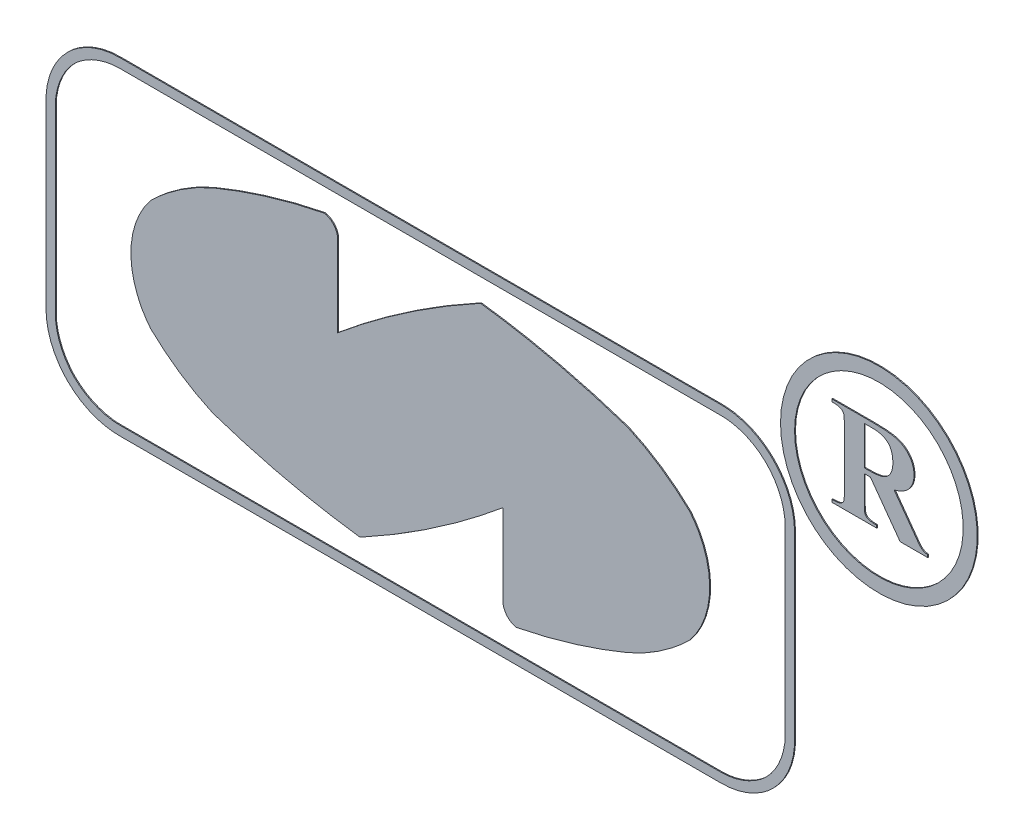
SolidWorks part; units mm, degrees
ref_plane "Спереди" through (0, 0, 0) normal (0, 0, 1) x (1, 0, 0)
ref_plane "Сверху" through (0, 0, 0) normal (0, 1, 0) x (1, 0, 0)
ref_plane "Справа" through (0, 0, 0) normal (1, 0, 0) x (0, 0, -1)
sketch "Эскиз1" plane through (0, 0, 0) normal (0, 0, 1) x (1, 0, 0)
  line L0 (3.1861, 1.7736) -> (-3.2358, 1.7736)
  line L1 (-4.0201, 0.9894) -> (-4.0201, -0.94)
  line L2 (-3.2358, -1.7242) -> (3.1861, -1.7242)
  line L3 (3.97, -0.94) -> (3.97, 0.9894)
  line L4 (-3.233, -1.7326) -> (3.1904, -1.7326)
  line L5 (-4.0213, 0.9865) -> (-4.0213, -0.9443)
  line L6 (3.1904, 1.7748) -> (-3.233, 1.7748)
  line L7 (3.9787, -0.9443) -> (3.9787, 0.9865)
  line L8 (3.1861, 1.6736) -> (-3.2358, 1.6736)
  line L9 (-3.9201, 0.9894) -> (-3.9201, -0.94)
  line L10 (-3.2358, -1.6242) -> (3.1861, -1.6242)
  line L11 (3.87, -0.94) -> (3.87, 0.9894)
  line L12 (4.2935, 1.4733) -> (5.4465, 1.4733) construction
  line L13 (-4.0201, 0.0247) -> (-3.9201, 0.0247) construction
  line L14 (-3.9201, 0.0247) -> (3.87, 0.0247) construction
  line L15 (3.87, 0.0247) -> (3.97, 0.0247) construction
  line L16 (4.87, 1.4733) -> (4.87, 1.9247) construction
  circle A0 centre (4.87, 1.9247) radius 0.9
  circle A1 centre (4.87, 1.9247) radius 1.05
  spline S0 degree 3 poles (-3.2358, 1.7736) (-3.444, 1.7736) (-3.6433, 1.6909) (-3.7904, 1.544) knots 0 0 0 0 0.5 0.5 0.5 0.5
  spline S1 degree 3 poles (-3.7904, 1.544) (-3.9374, 1.3968) (-4.0201, 1.1976) (-4.0201, 0.9894) knots 0.5 0.5 0.5 0.5 1 1 1 1
  spline S2 degree 3 poles (-4.0201, -0.94) (-4.0201, -1.1481) (-3.9374, -1.3474) (-3.7904, -1.4946) knots 0 0 0 0 0.5 0.5 0.5 0.5
  spline S3 degree 3 poles (-3.7904, -1.4946) (-3.6433, -1.6415) (-3.444, -1.7242) (-3.2358, -1.7242) knots 0.5 0.5 0.5 0.5 1 1 1 1
  spline S4 degree 3 poles (3.1861, -1.7242) (3.3941, -1.7242) (3.5937, -1.6415) (3.7405, -1.4946) knots 0 0 0 0 0.5 0.5 0.5 0.5
  spline S5 degree 3 poles (3.7405, -1.4946) (3.8876, -1.3474) (3.97, -1.1481) (3.97, -0.94) knots 0.5 0.5 0.5 0.5 1 1 1 1
  spline S6 degree 3 poles (3.97, 0.9894) (3.97, 1.4226) (3.6193, 1.7736) (3.1861, 1.7736) knots 0 0 0 0 1 1 1 1
  spline S7 degree 3 poles (3.1904, -1.7326) (3.3992, -1.7326) (3.6, -1.6494) (3.7476, -1.5017) knots 0 0 0 0 0.5 0.5 0.5 0.5
  spline S8 degree 3 poles (3.7476, -1.5017) (3.8954, -1.3538) (3.9787, -1.1533) (3.9787, -0.9443) knots 0.5 0.5 0.5 0.5 1 1 1 1
  spline S9 degree 3 poles (-4.0213, -0.9443) (-4.0213, -1.1533) (-3.9381, -1.3538) (-3.7904, -1.5017) knots 0 0 0 0 0.5 0.5 0.5 0.5
  spline S10 degree 3 poles (-3.7904, -1.5017) (-3.6426, -1.6494) (-3.4421, -1.7326) (-3.233, -1.7326) knots 0.5 0.5 0.5 0.5 1 1 1 1
  spline S11 degree 3 poles (-3.233, 1.7748) (-3.4421, 1.7748) (-3.6426, 1.6916) (-3.7904, 1.544) knots 0 0 0 0 0.5 0.5 0.5 0.5
  spline S12 degree 3 poles (-3.7904, 1.544) (-3.9381, 1.3961) (-4.0213, 1.1956) (-4.0213, 0.9865) knots 0.5 0.5 0.5 0.5 1 1 1 1
  spline S13 degree 3 poles (3.9787, 0.9865) (3.9787, 1.4221) (3.6259, 1.7748) (3.1904, 1.7748) knots 0 0 0 0 1 1 1 1
  spline S14 degree 3 poles (0.9967, -1.3782) (1.4053, -1.2975) (1.8056, -1.1761) (2.1907, -1.0161) knots 0 0 0 0 1 1 1 1
  spline S15 degree 3 poles (0.8579, -0.3419) (0.8571, -0.6292) (0.8567, -0.9163) (0.8567, -1.2034) knots 0 0 0 0 1 1 1 1
  spline S16 degree 3 poles (-0.6679, -1.3782) (-0.1262, -1.0837) (0.3846, -0.7366) (0.8579, -0.3419) knots 0 0 0 0 1 1 1 1
  spline S17 degree 3 poles (-2.2404, -1.0161) (-1.7292, -1.1883) (-1.2029, -1.3097) (-0.6679, -1.3782) knots 0 0 0 0 1 1 1 1
  spline S18 degree 3 poles (0.8567, -1.2034) (0.8567, -1.2872) (0.9147, -1.3597) (0.9967, -1.3782) knots 0 0 0 0 1 1 1 1
  spline S19 degree 3 poles (-2.9025, 0.6182) (-3.1842, 0.2726) (-3.1842, -0.2231) (-2.9025, -0.5684) knots 0 0 0 0 1 1 1 1
  spline S20 degree 3 poles (-2.2404, 1.0655) (-2.4868, 0.9579) (-2.711, 0.8066) (-2.9025, 0.6182) knots 0 0 0 0 1 1 1 1
  spline S21 degree 3 poles (-1.0459, 1.4276) (-1.4554, 1.347) (-1.8555, 1.2255) (-2.2404, 1.0655) knots 0 0 0 0 1 1 1 1
  spline S22 degree 3 poles (-0.9061, 1.2538) (-0.9069, 1.3373) (-0.9647, 1.4091) (-1.0459, 1.4276) knots 0 0 0 0 1 1 1 1
  spline S23 degree 3 poles (-0.9061, 1.2538) (-0.9072, 0.9665) (-0.9077, 0.6789) (-0.9077, 0.3913) knots 0 0 0 0 1 1 1 1
  spline S24 degree 3 poles (0.6183, 1.4276) (0.0768, 1.1332) (-0.4347, 0.786) (-0.9077, 0.3913) knots 0 0 0 0 1 1 1 1
  spline S25 degree 3 poles (2.1907, 1.0655) (1.6796, 1.2378) (1.153, 1.3591) (0.6183, 1.4276) knots 0 0 0 0 1 1 1 1
  spline S26 degree 3 poles (2.8527, 0.6182) (2.6593, 0.8043) (2.4356, 0.9552) (2.1907, 1.0655) knots 0 0 0 0 1 1 1 1
  spline S27 degree 3 poles (-2.9025, -0.5684) (-2.7089, -0.7549) (-2.4852, -0.9058) (-2.2404, -1.0161) knots 0 0 0 0 1 1 1 1
  spline S28 degree 3 poles (2.1907, -1.0161) (2.437, -0.9085) (2.6613, -0.7572) (2.8527, -0.5684) knots 0 0 0 0 1 1 1 1
  spline S29 degree 3 poles (2.8527, -0.5684) (3.1345, -0.2231) (3.1345, 0.2726) (2.8527, 0.6182) knots 0 0 0 0 1 1 1 1
  spline S30 degree 1 poles (-3.2358, 1.6736) (-3.7197, 1.4733) knots 0 0 1 1 construction
  spline S31 degree 1 poles (-3.7197, 1.4733) (-3.9201, 0.9894) knots 0 0 1 1 construction
  spline S32 degree 1 poles (-3.9201, -0.94) (-3.7197, -1.4239) knots 0 0 1 1 construction
  spline S33 degree 1 poles (-3.7197, -1.4239) (-3.2358, -1.6242) knots 0 0 1 1 construction
  spline S34 degree 1 poles (3.1861, -1.6242) (3.6698, -1.4239) knots 0 0 1 1 construction
  spline S35 degree 1 poles (3.6698, -1.4239) (3.87, -0.94) knots 0 0 1 1 construction
  spline S36 degree 1 poles (3.87, 0.9894) (3.1861, 1.6736) knots 0 0 1 1 construction
  spline S37 degree 3 poles (-3.2358, 1.6736) (-3.4104, 1.6736) (-3.5962, 1.5966) (-3.7197, 1.4733) knots 0 0 0 0 0.499938 0.499938 0.499938 0.499938
  spline S38 degree 3 poles (-3.7197, 1.4733) (-3.843, 1.3497) (-3.9201, 1.164) (-3.9201, 0.9894) knots 0.500062 0.500062 0.500062 0.500062 1 1 1 1
  spline S39 degree 3 poles (-3.9201, -0.94) (-3.9201, -1.1146) (-3.843, -1.3003) (-3.7197, -1.4239) knots 0 0 0 0 0.499938 0.499938 0.499938 0.499938
  spline S40 degree 3 poles (-3.7197, -1.4239) (-3.5962, -1.5472) (-3.4104, -1.6242) (-3.2358, -1.6242) knots 0.500062 0.500062 0.500062 0.500062 1 1 1 1
  spline S41 degree 3 poles (3.1861, -1.6242) (3.3606, -1.6242) (3.5464, -1.5473) (3.6698, -1.4239) knots 0 0 0 0 0.5 0.5 0.5 0.5
  spline S42 degree 3 poles (3.6698, -1.4239) (3.7932, -1.3004) (3.87, -1.1146) (3.87, -0.94) knots 0.5 0.5 0.5 0.5 1 1 1 1
  spline S43 degree 3 poles (3.87, 0.9894) (3.87, 1.164) (3.7242, 1.5277) (3.3606, 1.6736) (3.1861, 1.6736) knots 0 0 0 0 0.5 1 1 1 1
  point P57 (4.87, 1.4733)
  dimension "D2" = 1.8
  dimension "D3" = 0.15
  dimension "D4" = 0.9
  dimension "D1" = 0.1
extrude "Вытянуть1" add sketch "Эскиз1" along normal blind 0.01 contours S1 L1 S2 S3 L2 S4 S5 L3 S6 L0 S0 | S37 S38 L9 S39 S40 L10 S41 S42 L11 S43 L8 | S20 S19 S27 S17 S16 S15 S18 S14 S28 S29 S26 S25 S24 S23 S22 S21 | A1 | A0
sketch "Эскиз2" plane through (0, 0, 0.01) normal (0, 0, 1) x (1, 0, 0)
  line L0 (4.2935, 1.4733) -> (5.4465, 1.4733) construction
  text T0 "R" font "Times New Roman" height in points 4
extrude "Вытянуть2" add sketch "Эскиз2" along normal blind 0.01
